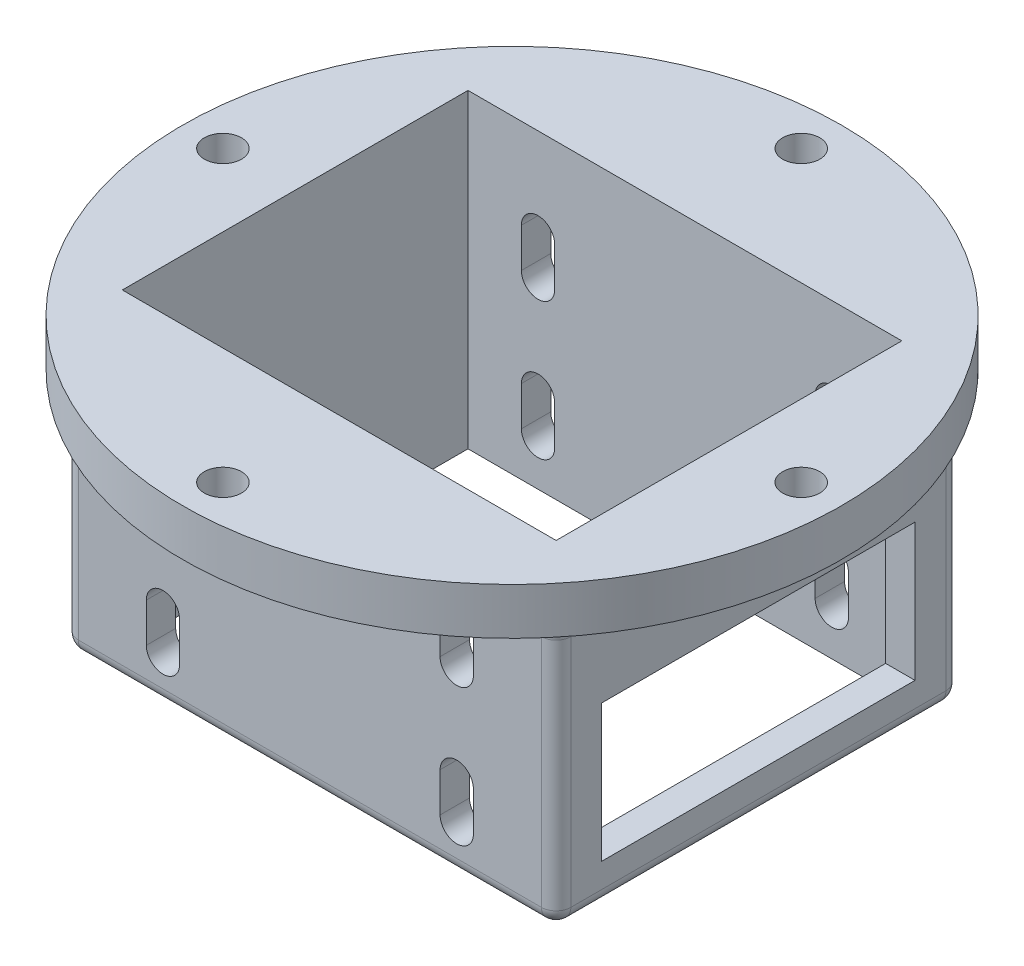
SolidWorks part; units mm, degrees
ref_plane "Front Plane" through (0, 0, 0) normal (0, 0, 1) x (1, 0, 0)
ref_plane "Top Plane" through (0, 0, 0) normal (0, 1, 0) x (1, 0, 0)
ref_plane "Right Plane" through (0, 0, 0) normal (1, 0, 0) x (0, 0, -1)
sketch "Sketch1" plane through (0, 0, 0) normal (0, 1, 0) x (1, 0, 0)
  circle A0 centre (0, 0) radius 33.655
  dimension "D1" = 67.31
extrude "Boss-Extrude1" add sketch "Sketch1" along normal blind 4.7625
sketch "Sketch2" plane through (0, 4.7625, 0) normal (0, 1, 0) x (1, 0, 0)
  line L1 (-25.15, -20.65) -> (25.15, -20.65)
  line L2 (-25.15, -20.65) -> (-25.15, 20.65)
  line L3 (-25.15, 20.65) -> (25.15, 20.65)
  line L4 (25.15, -20.65) -> (25.15, 20.65)
  line L5 (-25.15, -20.65) -> (25.15, 20.65) construction
  line L6 (-25.15, 20.65) -> (25.15, -20.65) construction
  point P0 (0, 0)
  dimension "D1" = 50.3
  dimension "D2" = 41.3
extrude "Boss-Extrude2" add sketch "Sketch2" against normal blind 31.7
hole_wizard "#6 Clearance Hole1" positions "Sketch5" profile "Sketch3" hole size "#6" standard "ANSI Inch" end condition through all
sketch "Sketch5" plane through (0, 4.7625, 0) normal (0, 1, 0) x (1, 0, 0)
  line L0 (0, 29.5275) -> (0, -29.5275) construction
  line L2 (-29.5275, 0) -> (29.5275, 0) construction
  point P0 (0, 29.5275)
  point P2 (29.5275, 0)
  point P4 (0, -29.5275)
  point P6 (-29.5275, 0)
  point P18 (0, 0)
  point P19 (0, 0)
  dimension "D1" = 59.055
  dimension "D2" = 59.055
sketch "Sketch3" plane through (0, 4.7625, -29.5275) normal (1, 0, 0) x (0, 0, 1)
  line L0 (0, 0) -> (0, 31.7)
  line L1 (0, 31.7) -> (1.8986, 31.7)
  line L2 (1.8986, 31.7) -> (1.8986, 0)
  line L5 (1.8986, 0) -> (0, 0)
  line L11 (0, -6.35) -> (0, 107.95) construction
  dimension "Thru Hole Dia." = 3.7973
  dimension "Thru Hole Depth" = 31.7
sketch "Sketch6" plane through (0, 4.7625, 0) normal (0, 1, 0) x (1, 0, 0)
  line L1 (-22.15, -17.65) -> (22.15, -17.65)
  line L2 (-22.15, -17.65) -> (-22.15, 17.65)
  line L3 (-22.15, 17.65) -> (22.15, 17.65)
  line L4 (22.15, -17.65) -> (22.15, 17.65)
  line L5 (-22.15, -17.65) -> (22.15, 17.65) construction
  line L6 (-22.15, 17.65) -> (22.15, -17.65) construction
  point P0 (0, 0)
  dimension "D1" = 44.3
  dimension "D2" = 35.3
extrude "Cut-Extrude1" cut sketch "Sketch6" against normal blind 28.7
sketch "Sketch7" plane through (25.15, 0, 0) normal (1, 0, 0) x (0, 0, -1)
  line L0 (-20.65, -26.9375) -> (20.65, -26.9375) construction
  line L1 (-16, -22.9375) -> (16, -22.9375)
  line L2 (-16, -22.9375) -> (-16, -8.9375)
  line L3 (-16, -8.9375) -> (16, -8.9375)
  line L4 (16, -22.9375) -> (16, -8.9375)
  line L5 (-16, -22.9375) -> (16, -8.9375) construction
  line L6 (-16, -8.9375) -> (16, -22.9375) construction
  point P0 (0, -15.9375)
  point P7 (0, -26.9375)
  dimension "D1" = 32
  dimension "D2" = 14
  dimension "D3" = 4
extrude "Cut-Extrude2" cut sketch "Sketch7" against normal up to surface (3 mm away) up to face at (22.15, -9.5875, 0)
fillet "Fillet1" radius 1.5 12 edges at (0, 0, -20.65) (-25.15, 0, 0) (25.15, 0, 0) (25.15, -26.9375, 0) (0, -26.9375, -20.65) (-25.15, -26.9375, 0) (0, -26.9375, 20.65) (-25.15, -13.4688, 20.65) (-25.15, -13.4688, -20.65) (25.15, -13.4688, -20.65) (25.15, -13.4688, 20.65) (0, 0, 20.65)
sketch "Sketch14" plane through (0, 0, -20.65) normal (0, 0, 1) x (1, 0, 0)
  line L0 (0, 0) -> (0, -25.4375) construction
  line L1 (-15, -6.4375) -> (15, -6.4375) construction
  line L2 (33.655, 4.7625) -> (-33.655, 4.7625) construction
  line L3 (-15, -20.4375) -> (15, -20.4375) construction
  line L4 (23.65, -25.4375) -> (-23.65, -25.4375) construction
  line L5 (15, -8.4375) -> (15, -4.4375) construction
  line L6 (13.3, -8.4375) -> (13.3, -4.4375)
  line L7 (16.7, -8.4375) -> (16.7, -4.4375)
  line L8 (-15, -6.4375) -> (-15, -20.4375) construction
  line L9 (15, -6.4375) -> (15, -20.4375) construction
  arc A0 (13.3, -8.4375) -> (16.7, -8.4375) centre (15, -8.4375) ccw
  arc A1 (16.7, -4.4375) -> (13.3, -4.4375) centre (15, -4.4375) ccw
  point P0 (-15, -6.4375)
  point P2 (-15, -20.4375)
  point P4 (15, -20.4375)
  point P6 (15, -6.4375)
  point P14 (15, -6.4375)
  point P19 (0, -6.4375)
  point P20 (0, -20.4375)
  dimension "D5" = 4
  dimension "D1" = 14
  dimension "D2" = 30
  dimension "D3" = 11.2
  dimension "D4" = 3.4
extrude "Cut-Extrude3" cut sketch "Sketch14" along normal through all
mirror "Mirror1" about plane through (0, 0, 0) normal (1, 0, 0) of "Cut-Extrude3"
ref_plane "Plane1" through (0, -13.4375, 0) normal (0, 1, 0) x (1, 0, 0)
mirror "Mirror2" about plane through (0, -13.4375, 0) normal (0, 1, 0) of "Mirror1", "Cut-Extrude3", "Cut-Extrude1"
